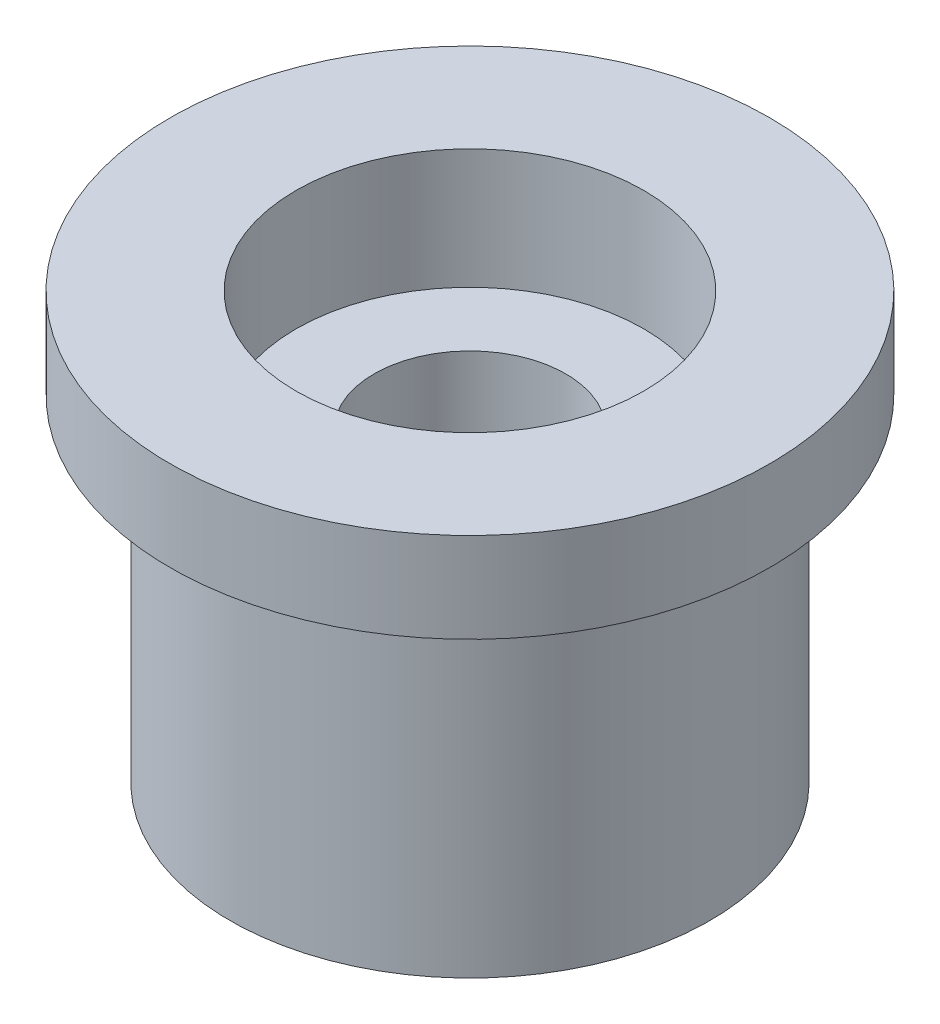
SolidWorks part; units mm, degrees
ref_plane "정면" through (0, 0, 0) normal (0, 0, 1) x (1, 0, 0)
ref_plane "윗면" through (0, 0, 0) normal (0, 1, 0) x (1, 0, 0)
ref_plane "우측면" through (0, 0, 0) normal (1, 0, 0) x (0, 0, -1)
sketch "스케치1" plane through (0, 0, 0) normal (0, 0, 1) x (1, 0, 0)
  line L0 (5, 7.1) -> (0, 7.1)
  line L1 (0, 7.1) -> (0, 5.6)
  line L2 (0, 5.6) -> (5, 5.6)
  line L3 (5, 5.6) -> (5, 7.1)
  line L4 (0, 7.1) -> (0, 5.6) construction
revolve "회전1" add sketch "스케치1" angle 360 about L4
sketch "스케치2" plane through (0, 5.6, 0) normal (0, -1, 0) x (1, 0, 0)
  circle A0 centre (0, 0) radius 4
extrude "보스-돌출1" add sketch "스케치2" along normal blind 5.6
sketch "스케치3" plane through (0, 0, 0) normal (0, -1, 0) x (1, 0, 0)
  line L0 (-1.1906, 2.8622) -> (-0.7861, 2.1615)
  line L1 (2.265, 0.4) -> (3.0741, 0.4)
  arc A0 (-0.7861, 2.1615) -> (2.265, 0.4) centre (0, 0) cw
  arc A1 (3.0741, 0.4) -> (-1.1906, 2.8622) centre (0, 0) ccw
extrude "컷-돌출1" cut sketch "스케치3" against normal blind 4.3
sketch "스케치4" plane through (0, 0, 0) normal (0, -1, 0) x (1, 0, 0)
  line L0 (-0.7861, -2.1615) -> (-1.1906, -2.8622)
  line L1 (3.0741, -0.4) -> (2.265, -0.4)
  arc A0 (-1.1906, -2.8622) -> (3.0741, -0.4) centre (0, 0) ccw
  arc A1 (2.265, -0.4) -> (-0.7861, -2.1615) centre (0, 0) cw
extrude "컷-돌출2" cut sketch "스케치4" against normal blind 4.3
sketch "스케치5" plane through (0, 0, 0) normal (0, -1, 0) x (1, 0, 0)
  line L0 (-1.8835, -2.4622) -> (-1.4789, -1.7615)
  line L1 (-1.4789, 1.7615) -> (-1.8835, 2.4622)
  arc A0 (-1.4789, -1.7615) -> (-1.4789, 1.7615) centre (0, 0) cw
  arc A1 (-1.8835, 2.4622) -> (-1.8835, -2.4622) centre (0, 0) ccw
extrude "컷-돌출3" cut sketch "스케치5" against normal blind 4.3
hole_wizard "M3 육각 머리 작은 나사용 카운터보어1" positions "스케치7" profile "스케치6" counterbore size "M3" standard "Ansi Metric"
sketch "스케치7" plane through (0, 7.1, 0) normal (0, 1, 0) x (1, 0, 0)
  point P0 (0, 0)
sketch "스케치6" plane through (0, 7.1, 0) normal (1, 0, 0) x (0, 0, 1)
  line L0 (0, 0) -> (0, 7.1)
  line L1 (0, 7.1) -> (1.6, 7.1)
  line L3 (1.6, 7.1) -> (1.6, 2)
  line L4 (1.6, 2) -> (2.9, 2)
  line L5 (2.9, 2) -> (2.9, 0)
  line L7 (2.9, 0) -> (0, 0)
  line L11 (0, -6.35) -> (0, 107.95) construction
  dimension "관통 구멍 지름" = 3.2
  dimension "관통 구멍 깊이" = 7.1
  dimension "카운터보어 지름" = 5.8
  dimension "카운터보어 깊이" = 2
